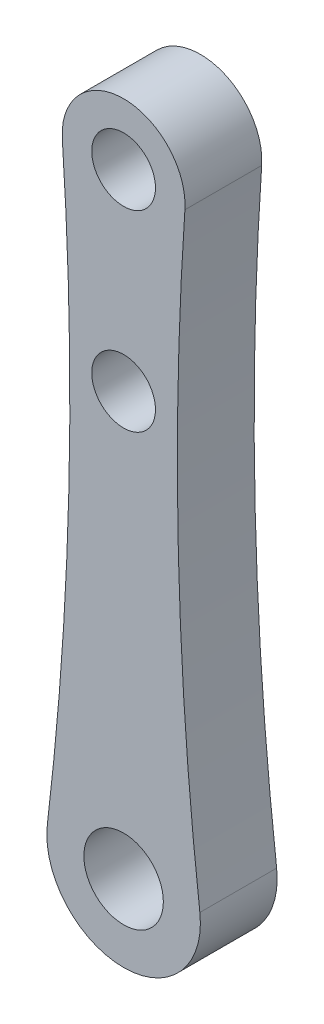
SolidWorks part; units mm, degrees
ref_plane "Front Plane" through (0, 0, 0) normal (0, 0, 1) x (1, 0, 0)
ref_plane "Top Plane" through (0, 0, 0) normal (0, 1, 0) x (1, 0, 0)
ref_plane "Right Plane" through (0, 0, 0) normal (1, 0, 0) x (0, 0, -1)
sketch "Sketch1" plane through (0, 0, 0) normal (0, 0, 1) x (1, 0, 0)
  line L0 (0, -40) -> (0, 40) construction
  arc A0 (7.9813, 39.4538) -> (-7.9813, 39.4538) centre (0, 40) ccw
  arc A1 (-9.9303, -38.8216) -> (9.9303, -38.8216) centre (0, -40) ccw
  circle A2 centre (0, -40) radius 5.175
  circle A3 centre (0, 40) radius 4.15
  circle A4 centre (0, 15) radius 4.15
  arc A5 (-9.9303, -38.8216) -> (-7.9813, 39.4538) centre (-427.5849, 10.7396) ccw
  arc A6 (9.9303, -38.8216) -> (7.9813, 39.4538) centre (427.5849, 10.7396) cw
  point P4 (0, 0)
  dimension "D1" = 20
  dimension "D2" = 16
  dimension "D3" = 8.3
  dimension "D4" = 10.35
  dimension "D5" = 80
  dimension "D6" = 55
  dimension "D7" = 14
extrude "Corpo" add sketch "Sketch1" along normal blind 10
